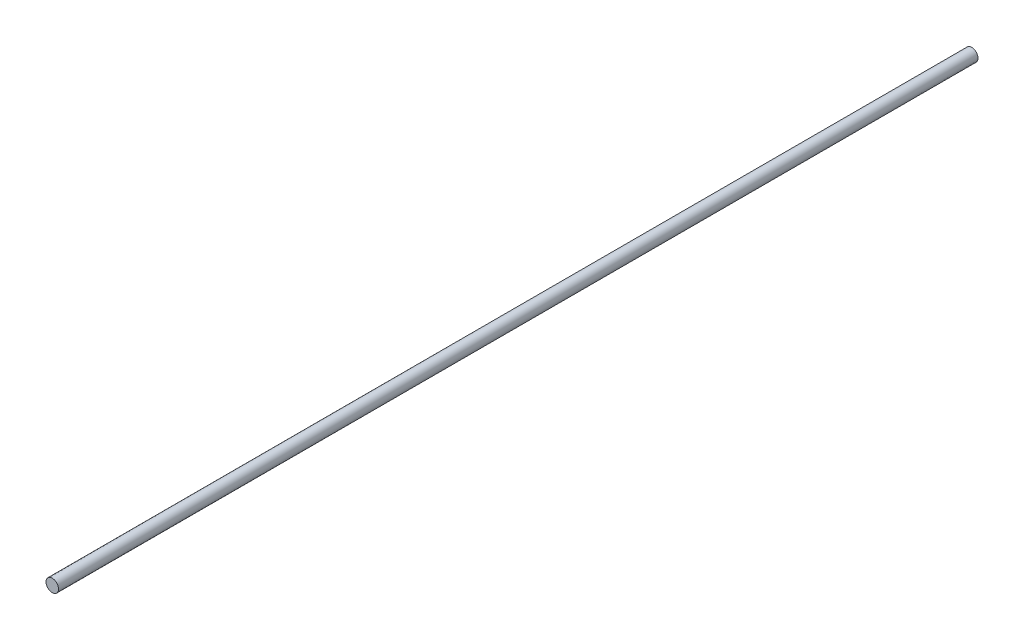
SolidWorks part; units mm, degrees
ref_plane "Plan de face" through (0, 0, 0) normal (0, 0, 1) x (1, 0, 0)
ref_plane "Plan de dessus" through (0, 0, 0) normal (0, 1, 0) x (1, 0, 0)
ref_plane "Plan de droite" through (0, 0, 0) normal (1, 0, 0) x (0, 0, -1)
sketch "Esquisse1" plane through (0, 0, 0) normal (0, 0, 1) x (1, 0, 0)
  circle A0 centre (0, 0) radius 3
  dimension "D1" = 6
extrude "Boss.-Extru.1" add sketch "Esquisse1" along normal blind 440
